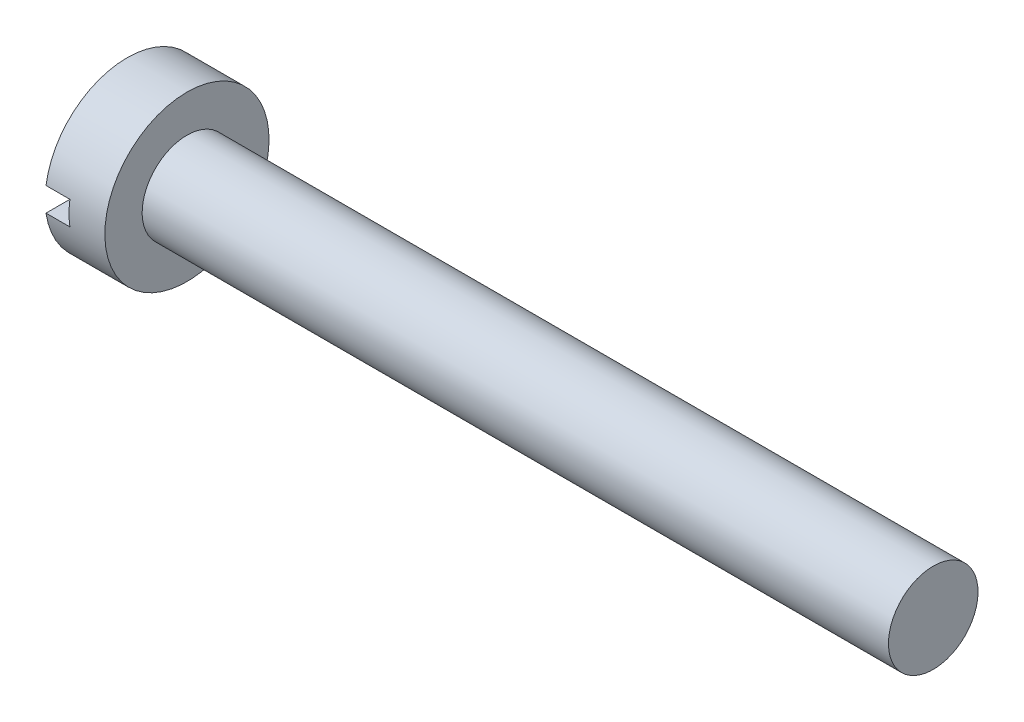
SolidWorks part; units mm, degrees
material "Plain Carbon Steel"
ref_plane "Front Plane" through (0, 0, 0) normal (0, 0, 1) x (1, 0, 0)
ref_plane "Top Plane" through (0, 0, 0) normal (0, 1, 0) x (1, 0, 0)
ref_plane "Right Plane" through (0, 0, 0) normal (1, 0, 0) x (0, 0, -1)
sketch "Sketch1" plane through (0, 0, 0) normal (0, 0, 1) x (1, 0, 0)
  line L0 (0, 0) -> (0, 2.75)
  line L1 (0, 2.75) -> (2, 2.75)
  line L2 (2, 2.75) -> (2, 1.5)
  line L3 (2, 1.5) -> (27, 1.5)
  line L4 (27, 1.5) -> (27, 0)
  line L5 (27, 0) -> (0, 0) construction
  line L6 (0, 0) -> (27, 0)
  dimension "D1" = 3
  dimension "D2" = 25
  dimension "D3" = 5.5
  dimension "D4" = 2
revolve "Revolve1" add sketch "Sketch1" angle 360 about L5
sketch "Sketch2" plane through (0, 0, 0) normal (-1, 0, 0) x (0, 0, 1)
  line L0 (2.75, 0) -> (-2.75, 0) construction
  line L1 (-2.75, 0.4) -> (2.75, 0.4)
  line L2 (-2.75, 0.4) -> (-2.75, -0.4)
  line L3 (-2.75, -0.4) -> (2.75, -0.4)
  line L4 (2.75, 0.4) -> (2.75, -0.4)
  circle A0 centre (0, 0) radius 2.75 construction
  dimension "D1" = 0.8
extrude "Cut-Extrude1" cut sketch "Sketch2" against normal blind 0.8
